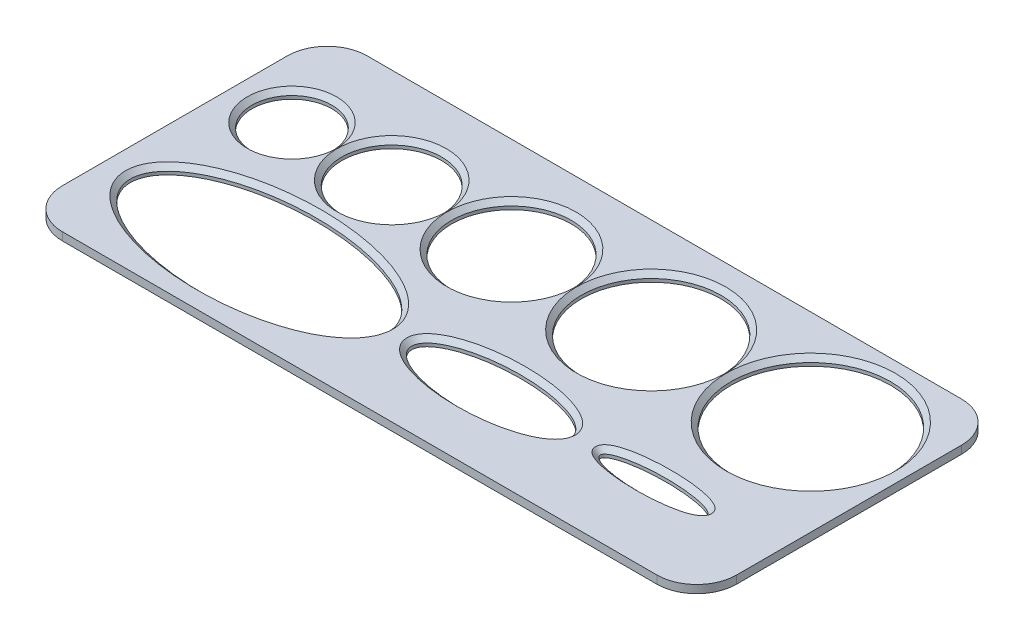
SolidWorks part; units mm, degrees
ref_plane "Front Plane" through (0, 0, 0) normal (0, 0, 1) x (1, 0, 0)
ref_plane "Top Plane" through (0, 0, 0) normal (0, 1, 0) x (1, 0, 0)
ref_plane "Right Plane" through (0, 0, 0) normal (1, 0, 0) x (0, 0, -1)
sketch "Sketch1" plane through (0, 0, 0) normal (0, 1, 0) x (1, 0, 0)
  line L1 (104.3603, 41.8744) -> (-44.5583, 41.8744)
  line L2 (114.3603, 31.8744) -> (114.3603, -24.473)
  line L3 (104.3603, -34.473) -> (-44.5583, -34.473)
  line L4 (-54.5583, 31.8744) -> (-54.5583, -24.473)
  circle A0 centre (-39.497, 17.9633) radius 10
  circle A1 centre (-14.497, 17.9633) radius 12.5
  circle A2 centre (15.503, 17.9633) radius 15
  circle A3 centre (50.503, 17.9633) radius 17.5
  circle A4 centre (90.503, 17.9633) radius 20
  arc A5 (-44.5583, -34.473) -> (-54.5583, -24.473) centre (-44.5583, -24.473) cw
  arc A6 (114.3603, -24.473) -> (104.3603, -34.473) centre (104.3603, -24.473) cw
  arc A7 (104.3603, 41.8744) -> (114.3603, 31.8744) centre (104.3603, 31.8744) cw
  arc A8 (-44.5583, 41.8744) -> (-54.5583, 31.8744) centre (-44.5583, 31.8744) ccw
  ellipse E0 centre (-15.9672, -13.7511) end of major axis (16.7715, -14.3306) minor radius 15.2822
  ellipse E1 centre (42.6963, -14.3306) end of major axis (62.5922, -14.3306) minor radius 7.4106
  ellipse E2 centre (83.3776, -14.3306) end of major axis (70.0375, -14.3306) minor radius 3.1784
  point P32 (114.3603, 41.5563)
  point P33 (-54.5583, 41.8744)
  dimension "D1" = 20
  dimension "D2" = 25
  dimension "D3" = 30
  dimension "D4" = 35
  dimension "D5" = 55
  dimension "D6" = 35
  dimension "D7" = 40
  dimension "D8" = 40
  dimension "D9" = 10
extrude "Boss-Extrude1" add sketch "Sketch1" along normal blind 2
chamfer "Chamfer1" distance 1.2 angle 45 8 edges at (96.7177, 2, 14.3306) (62.5922, 2, 14.3306) (16.7715, 2, 14.3306) (90.503, 2, 2.0367) (50.503, 2, -0.4633) (15.503, 2, -2.9633) (-14.497, 2, -5.4633) (-39.497, 2, -7.9633)
